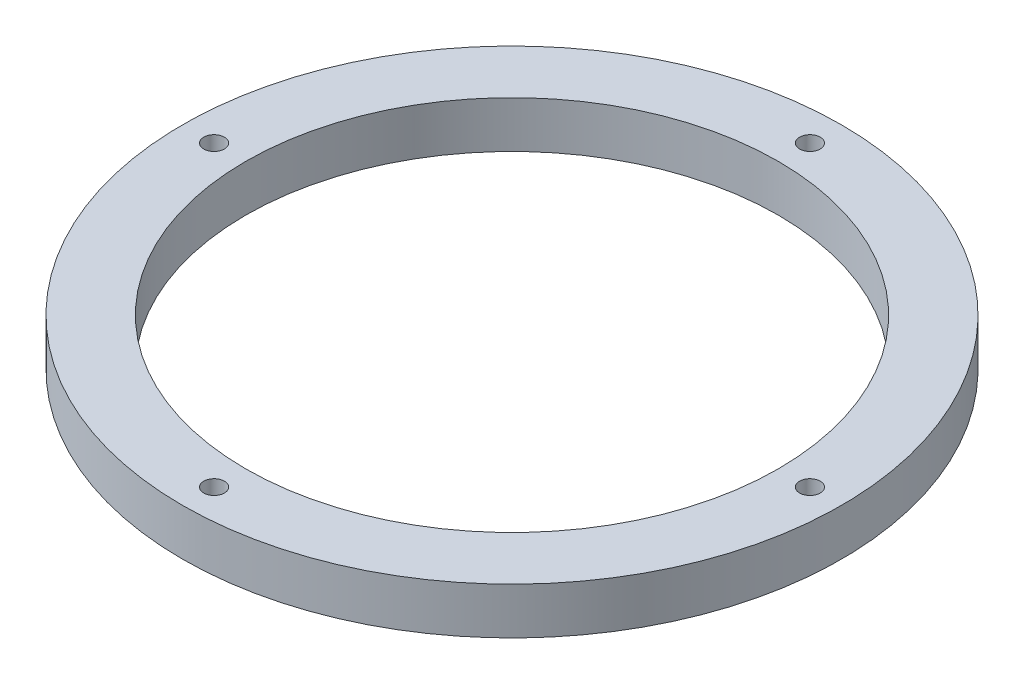
SolidWorks part; units mm, degrees
ref_plane "前视基准面" through (0, 0, 0) normal (0, 0, 1) x (1, 0, 0)
ref_plane "上视基准面" through (0, 0, 0) normal (0, 1, 0) x (1, 0, 0)
ref_plane "右视基准面" through (0, 0, 0) normal (1, 0, 0) x (0, 0, -1)
sketch "草图1" plane through (0, 0, 0) normal (0, 1, 0) x (1, 0, 0)
  circle A0 centre (0, 0) radius 40
  circle A1 centre (0, 0) radius 49.5
extrude "凸台-拉伸1" add sketch "草图1" along normal blind 7
sketch "草图2" plane through (0, 7, 0) normal (0, 1, 0) x (1, 0, 0)
  circle A0 centre (0, 0) radius 44.75 construction
  circle A1 centre (-44.75, 0) radius 1.55
  circle A2 centre (0, 44.75) radius 1.55
  circle A3 centre (44.75, 0) radius 1.55
  circle A4 centre (0, -44.75) radius 1.55
  point P14 (0, 0)
  dimension "D1" = 4
extrude "切除-拉伸1" cut sketch "草图2" against normal blind 7
